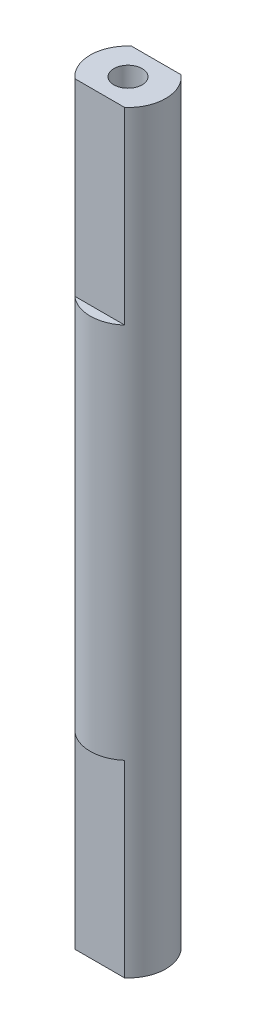
SolidWorks part; units mm, degrees
ref_plane "Alzado" through (0, 0, 0) normal (0, 0, 1) x (1, 0, 0)
ref_plane "Planta" through (0, 0, 0) normal (0, 1, 0) x (1, 0, 0)
ref_plane "Vista lateral" through (0, 0, 0) normal (1, 0, 0) x (0, 0, -1)
sketch "Croquis1" plane through (0, 0, 0) normal (0, 1, 0) x (1, 0, 0)
  circle A0 centre (0, 0) radius 2
  dimension "D1" = 4
extrude "Saliente-Extruir1" add sketch "Croquis1" along normal mid plane 20
sketch "Croquis2" plane through (0, 10, 0) normal (0, 1, 0) x (1, 0, 0)
  line L0 (1.3229, 1.5) -> (-1.3229, 1.5)
  line L2 (1.3229, -1.5) -> (-1.3229, -1.5)
  arc A0 (1.3229, -1.5) -> (1.3229, 1.5) centre (0, 0) ccw
  circle A1 centre (0, 0) radius 2
  arc A2 (-1.3229, 1.5) -> (-1.3229, -1.5) centre (0, 0) ccw
  dimension "D2" = 1.5
  dimension "D3" = 1.5
  dimension "D1" = 0
extrude "Saliente-Extruir2" add sketch "Croquis2" along normal blind 10
sketch "Croquis3" plane through (0, 20, 0) normal (0, 1, 0) x (1, 0, 0)
  circle A0 centre (0, 0) radius 0.75
  dimension "D1" = 1.5
extrude "Cortar-Extruir1" cut sketch "Croquis3" against normal blind 8
mirror "Simetría1" about plane through (0, 0, 0) normal (0, 1, 0) of "Saliente-Extruir2", "Cortar-Extruir1"
